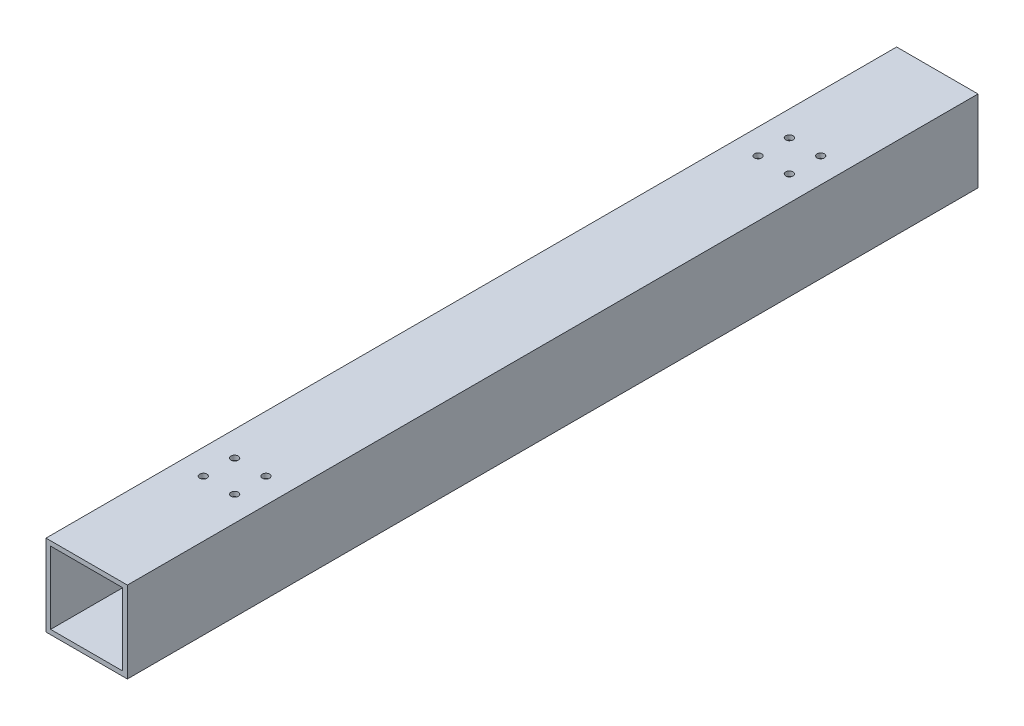
SolidWorks part; units mm, degrees
ref_plane "Front Plane" through (0, 0, 0) normal (0, 0, 1) x (1, 0, 0)
ref_plane "Top Plane" through (0, 0, 0) normal (0, 1, 0) x (1, 0, 0)
ref_plane "Right Plane" through (0, 0, 0) normal (1, 0, 0) x (0, 0, -1)
sketch "Sketch1" plane through (0, 0, 0) normal (0, 0, 1) x (1, 0, 0)
  line L1 (-17.4625, -17.4625) -> (17.4625, -17.4625)
  line L2 (-17.4625, -17.4625) -> (-17.4625, 17.4625)
  line L3 (-17.4625, 17.4625) -> (17.4625, 17.4625)
  line L4 (17.4625, -17.4625) -> (17.4625, 17.4625)
  line L5 (-17.4625, -17.4625) -> (17.4625, 17.4625) construction
  line L6 (-17.4625, 17.4625) -> (17.4625, -17.4625) construction
  line L7 (-15.4813, -15.4813) -> (15.4813, -15.4813)
  line L8 (-15.4813, -15.4813) -> (-15.4813, 15.4813)
  line L9 (-15.4813, 15.4813) -> (15.4813, 15.4813)
  line L10 (15.4813, -15.4813) -> (15.4813, 15.4813)
  line L11 (-15.4813, -15.4813) -> (15.4813, 15.4813) construction
  line L12 (-15.4813, 15.4813) -> (15.4813, -15.4813) construction
  point P0 (0, 0)
  point P5 (0, 0)
  dimension "D1" = 34.925
  dimension "D2" = 30.9626
extrude "Boss-Extrude1" add sketch "Sketch1" along normal mid plane 365.125
sketch "Sketch2" plane through (0, 0, 0) normal (0, 1, 0) x (1, 0, 0)
  line L0 (6.7175, 125.78) -> (-6.7175, 112.345) construction
  line L1 (-6.7175, 125.78) -> (6.7175, 112.345) construction
  line L3 (17.4625, -182.5625) -> (17.4625, 182.5625) construction
  line L4 (17.4625, 182.5625) -> (-17.4625, 182.5625) construction
  line L5 (-19.2087, 0) -> (19.2087, 0) construction
  line L6 (-6.7175, -125.78) -> (6.7175, -112.345) construction
  line L7 (6.7175, -125.78) -> (-6.7175, -112.345) construction
  circle A0 centre (-6.7175, 125.78) radius 1.5625
  circle A1 centre (6.7175, 125.78) radius 1.5625
  circle A2 centre (6.7175, 112.345) radius 1.5625
  circle A3 centre (-6.7175, 112.345) radius 1.5625
  circle A4 centre (-6.7175, -112.345) radius 1.5625
  circle A5 centre (6.7175, -112.345) radius 1.5625
  circle A6 centre (6.7175, -125.78) radius 1.5625
  circle A7 centre (-6.7175, -125.78) radius 1.5625
  point P6 (0, 119.0625)
  point P7 (0, 119.0625)
  dimension "D4" = 3.125
  dimension "D1" = 19
  dimension "D2" = 45
  dimension "D3" = 63.5
extrude "Cut-Extrude1" cut sketch "Sketch2" against normal through all and the other way through all
equation "\"D2@Sketch1\"=\"id\""
equation "\"D1@Sketch1\"=\"od\""
equation "\"od\"= 1.375in"
equation "\"id\"= \"od\" - ( .078 * 2 )"
equation "\"length\"= 14.375in"
equation "\"D1@Boss-Extrude1\"=\"length\""
equation "\"thruster hole (oversized)\"= 3.125mm"
equation "\"D4@Sketch2\"=\"thruster hole (oversized)\""
